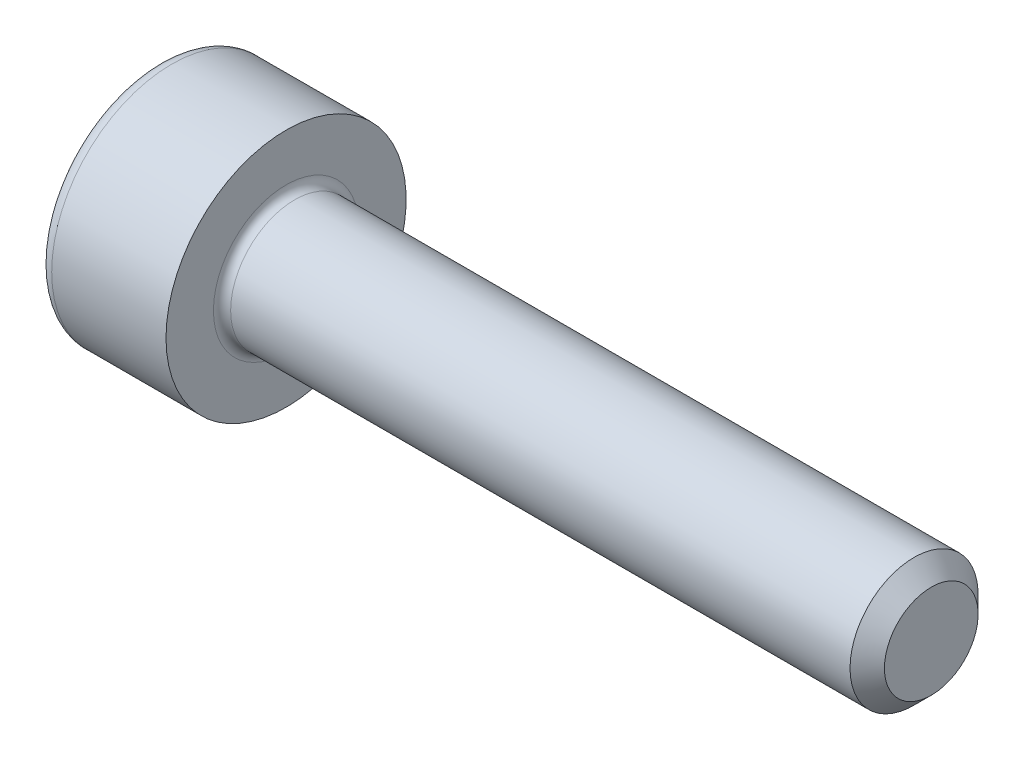
SolidWorks part; units mm, degrees
ref_plane "Спереди" through (0, 0, 0) normal (0, 0, 1) x (1, 0, 0)
ref_plane "Сверху" through (0, 0, 0) normal (0, 1, 0) x (1, 0, 0)
ref_plane "Справа" through (0, 0, 0) normal (1, 0, 0) x (0, 0, -1)
sketch "Sketch1" plane through (0, 0, 0) normal (0, 0, 1) x (1, 0, 0)
  line L0 (0, 0) -> (1.4887, 0)
  line L1 (1.4887, 0) -> (1.4887, 1.3957)
  line L2 (1.4887, 1.3957) -> (0, 1.3957)
  line L3 (0, 1.3957) -> (0, 0)
  line L4 (1.4887, 0) -> (8.9887, 0)
  line L5 (8.9887, 0) -> (8.9887, 0.7444)
  line L6 (8.9887, 0.7444) -> (1.4887, 0.7444)
  dimension "D1" = 7.5
revolve "Revolve1" add sketch "Sketch1" angle 360 about L0
fillet "Fillet1" radius 0.1 1 edges at (1.4887, 0, 0.7444)
fillet "Fillet2" radius 0.16 1 edges at (0, 0, 1.3957)
chamfer "Chamfer1" distance 0.2 angle 45 1 edges at (8.9887, 0, 0.7444)
sketch "Sketch2" plane through (0, 0, 0) normal (-1, 0, 0) x (0, 0, 1)
  line L1 (0, 0.8776) -> (-0.76, 0.4388)
  line L2 (-0.76, 0.4388) -> (-0.76, -0.4388)
  line L3 (-0.76, -0.4388) -> (0, -0.8776)
  line L4 (0, -0.8776) -> (0.76, -0.4388)
  line L5 (0.76, -0.4388) -> (0.76, 0.4388)
  line L6 (0.76, 0.4388) -> (0, 0.8776)
  circle A0 centre (0, 0) radius 0.76 construction
extrude "Extrude1" cut sketch "Sketch2" against normal blind 0.7
